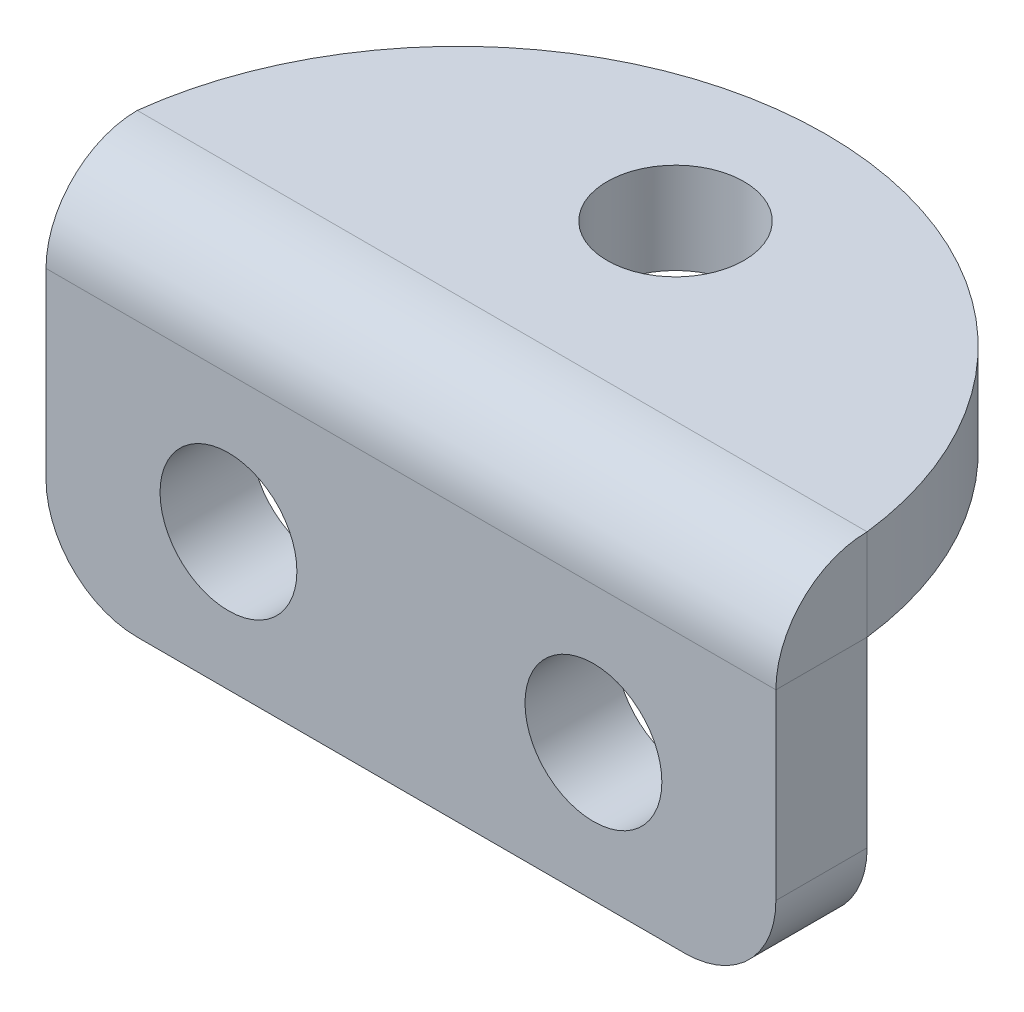
SolidWorks part; units mm, degrees
ref_plane "Front Plane" through (0, 0, 0) normal (0, 0, 1) x (1, 0, 0)
ref_plane "Top Plane" through (0, 0, 0) normal (0, 1, 0) x (1, 0, 0)
ref_plane "Right Plane" through (0, 0, 0) normal (1, 0, 0) x (0, 0, -1)
sketch "Sketch1" plane through (0, 0, 0) normal (0, 0, 1) x (1, 0, 0)
  line L0 (0, 0) -> (0, -4)
  line L1 (2, -6) -> (14, -6)
  line L2 (16, -4) -> (16, 0)
  line L3 (16, 0) -> (0, 0)
  arc A0 (0, -4) -> (2, -6) centre (2, -4) ccw
  arc A1 (16, -4) -> (14, -6) centre (14, -4) cw
  dimension "D1" = 4
  dimension "D4" = 2
  dimension "D2" = 12
  dimension "D3" = 16
  dimension "D5" = 4
extrude "Boss-Extrude1" add sketch "Sketch1" along normal blind 2
sketch "Sketch5" plane through (0, 0, 0) normal (0, 1, 0) x (1, 0, 0)
  line L1 (0, 0) -> (0, -2)
  line L2 (0, -2) -> (16, -2)
  line L3 (16, -2) -> (16, 0)
  arc A1 (0, 0) -> (16, 0) centre (8, -0.9598) cw
  dimension "D1" = 8.0574
extrude "Boss-Extrude2" add sketch "Sketch5" along normal blind 2 separate body
sketch "Sketch10" plane through (0, 0, 0) normal (0, 0, -1) x (-1, 0, 0)
  line L0 (-16, -4) -> (-16, 0) construction
  line L1 (0, 0) -> (0, -4) construction
  line L2 (-2, -6) -> (-14, -6) construction
  circle A0 centre (-12, -3) radius 1.5
  circle A1 centre (-4, -3) radius 1.5
  dimension "D1" = 3
  dimension "D2" = 3
  dimension "D3" = 4
  dimension "D4" = 4
  dimension "D5" = 3
  dimension "D6" = 3
extrude "Cut-Extrude3" cut sketch "Sketch10" against normal blind 6
sketch "Sketch11" plane through (0, 0, 0) normal (1, 0, 0) x (0, 0, -1)
  line L0 (-2, 0) -> (-2, -4) construction
  line L1 (0, 2) -> (-2, 2)
  line L2 (-2, 2) -> (-2, 0) construction
  line L3 (-2, 2) -> (-2, 0)
  arc A0 (0, 2) -> (-2, 0) centre (0, 0) ccw
extrude "Cut-Extrude4" cut sketch "Sketch11" along normal blind 16
sketch "Sketch12" plane through (0, 0, 0) normal (0, 1, 0) x (1, 0, 0)
  line L0 (0, 0) -> (21.719, 0) construction
  line L1 (8, 9.1793) -> (8, -6.9938)
  circle A0 centre (8, 3.8) radius 1.5
  dimension "D2" = 5.8
  dimension "D3" = 3
  dimension "D1" = 8
extrude "Cut-Extrude5" cut sketch "Sketch12" along normal blind 16 contours A0
